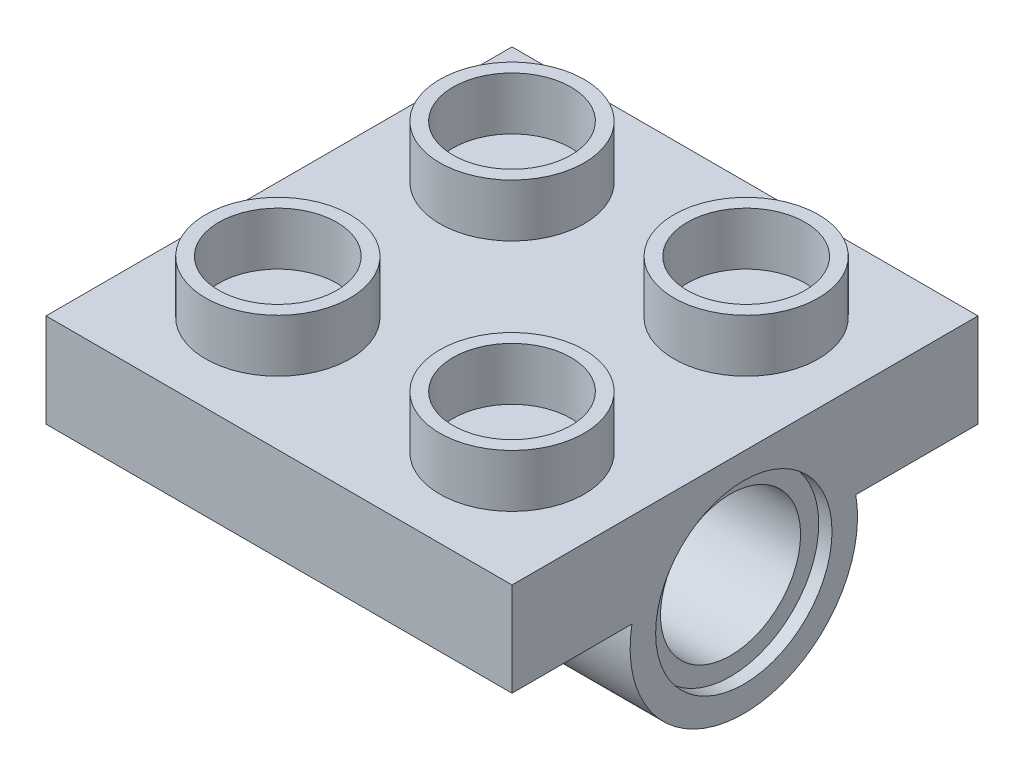
SolidWorks part; units mm, degrees
ref_plane "Front Plane" through (0, 0, 0) normal (0, 0, 1) x (1, 0, 0)
ref_plane "Top Plane" through (0, 0, 0) normal (0, 1, 0) x (1, 0, 0)
ref_plane "Right Plane" through (0, 0, 0) normal (1, 0, 0) x (0, 0, -1)
sketch "Sketch1" plane through (0, 0, 0) normal (0, 1, 0) x (1, 0, 0)
  line L1 (-7.9, 7.9) -> (7.9, 7.9)
  line L2 (-7.9, 7.9) -> (-7.9, -7.9)
  line L3 (-7.9, -7.9) -> (7.9, -7.9)
  line L4 (7.9, 7.9) -> (7.9, -7.9)
  line L5 (-7.9, 7.9) -> (7.9, -7.9) construction
  line L6 (-7.9, -7.9) -> (7.9, 7.9) construction
  point P0 (0, 0)
  dimension "D1" = 15.8
  dimension "D2" = 15.8
extrude "Boss-Extrude1" add sketch "Sketch1" against normal blind 7.71
sketch "Sketch2" plane through (7.9, 0, 0) normal (1, 0, 0) x (0, 0, -1)
  line L0 (-7.9, 0) -> (7.9, 0) construction
  line L2 (7.9, -7.71) -> (7.9, 0) construction
  circle A0 centre (-0.04, -3.855) radius 2.99
  dimension "D3" = 5.98
  dimension "D1" = 3.855
  dimension "D2" = 7.94
extrude "Cut-Extrude1" cut sketch "Sketch2" against normal blind 0.45
sketch "Sketch3" plane through (7.45, 0, 0) normal (1, 0, 0) x (0, 0, -1)
  line L0 (-7.9, 0) -> (7.9, 0) construction
  line L1 (7.9, -7.71) -> (7.9, 0) construction
  circle A0 centre (-0.04, -3.855) radius 2.375
  dimension "D2" = 7.94
  dimension "D3" = 4.75
  dimension "D1" = 3.855
extrude "Cut-Extrude2" cut sketch "Sketch3" against normal blind 6.56
sketch "Sketch4" plane through (7.9, 0, 0) normal (1, 0, 0) x (0, 0, -1)
  line L0 (-7.9, -3.18) -> (-3.8354, -3.18)
  line L1 (-7.9, -7.71) -> (-7.9, 0) construction
  line L2 (3.7554, -3.18) -> (7.9, -3.18)
  line L3 (7.9, -7.71) -> (7.9, 0) construction
  line L4 (-7.9, 0) -> (7.9, 0) construction
  arc A0 (-3.8354, -3.18) -> (3.7554, -3.18) centre (-0.04, -3.855) ccw
  dimension "D2" = 3.855
  dimension "D1" = 3.18
extrude "Cut-Extrude4" cut sketch "Sketch4" against normal through all and the other way through all flip side to cut
sketch "Sketch6" plane through (-7.9, 0, 0) normal (-1, 0, 0) x (0, 0, 1)
  line L0 (-3.7554, -3.18) -> (3.8354, -3.18)
extrude "Cut-Extrude5" cut sketch "Sketch6" against normal blind 8.87 and the other way through all flip side to cut
sketch "Sketch7" plane through (0, -3.18, 0) normal (0, -1, 0) x (1, 0, 0)
  line L2 (6.41, 6.33) -> (-0.33, 6.33)
  line L3 (-0.33, 6.33) -> (-0.33, -6.33)
  line L4 (-0.33, -6.33) -> (6.41, -6.33)
  line L19 (6.41, 6.33) -> (6.41, 4.0505)
  line L20 (6.41, 4.0505) -> (0.97, 4.0505)
  line L21 (0.97, 4.0505) -> (0.97, -4.2172)
  line L22 (0.97, -4.2172) -> (6.41, -4.2172)
  line L23 (6.41, -4.2172) -> (6.41, -6.33)
  line L24 (7.9, 3.8354) -> (7.9, 7.9) construction
  line L25 (7.9, 7.9) -> (-7.9, 7.9) construction
  line L26 (7.9, -7.9) -> (7.9, -3.7554) construction
  line L27 (-7.9, -7.9) -> (7.9, -7.9) construction
  dimension "D1" = 1.49
  dimension "D2" = 1.57
  dimension "D3" = 1.49
  dimension "D4" = 1.57
  dimension "D5" = 6.74
extrude "Cut-Extrude6" cut sketch "Sketch7" against normal blind 2.07
sketch "Sketch10" plane through (0, -3.18, 0) normal (0, -1, 0) x (1, 0, 0)
  line L0 (0.97, 3.8354) -> (0.97, 4.0505)
  line L1 (0.97, 4.0505) -> (6.41, 4.0505)
  line L2 (6.41, 4.0505) -> (6.41, 3.8354)
  line L3 (7.9, 3.8354) -> (0.97, 3.8354) construction
  line L4 (6.41, 3.8354) -> (0.97, 3.8354)
extrude "Cut-Extrude8" cut sketch "Sketch10" against normal up to surface (2.07 mm away) up to face at (3.365, -1.11, -0.0417)
sketch "Sketch11" plane through (0, -3.18, 0) normal (0, -1, 0) x (1, 0, 0)
  line L0 (6.41, -4.2172) -> (0.97, -4.2172)
  line L1 (0.97, -4.2172) -> (0.97, -3.7554)
  line L2 (0.97, -3.7554) -> (6.41, -3.7554)
  line L3 (7.9, -3.7554) -> (0.97, -3.7554) construction
  line L4 (6.41, -3.7554) -> (6.41, -4.2172)
extrude "Cut-Extrude9" cut sketch "Sketch11" against normal up to surface (2.07 mm away) up to face at (3.365, -1.11, -0.0954)
sketch "Sketch12" plane through (0, -3.18, 0) normal (0, -1, 0) x (1, 0, 0)
  line L0 (-6.41, 6.47) -> (-1.48, 6.47)
  line L1 (-1.48, 6.47) -> (-1.48, -6.47)
  line L2 (-1.48, -6.47) -> (-6.41, -6.47)
  line L3 (-6.41, -6.47) -> (-6.41, 6.47)
  line L4 (-0.33, 6.33) -> (-0.33, -6.33) construction
  line L5 (-7.9, 7.9) -> (-7.9, -7.9) construction
  line L6 (7.9, 7.9) -> (-7.9, 7.9) construction
  line L7 (-7.9, -7.9) -> (7.9, -7.9) construction
  dimension "D1" = 1.15
  dimension "D2" = 1.49
  dimension "D3" = 1.43
  dimension "D4" = 1.43
extrude "Cut-Extrude10" cut sketch "Sketch12" against normal blind 2.07
sketch "Sketch13" plane through (0, -1.11, 0) normal (0, -1, 0) x (1, 0, 0)
  line L1 (7.9, 7.9) -> (-7.9, 7.9) construction
  line L2 (-6.41, 6.47) -> (-6.41, -6.47) construction
  circle A0 centre (-3.985, -0.04) radius 1.425
  circle A1 centre (-3.985, -0.04) radius 1.1
  dimension "D1" = 7.94
  dimension "D2" = 2.85
  dimension "D3" = 2.425
  dimension "D4" = 2.2
extrude "Boss-Extrude2" add sketch "Sketch13" along normal offset from surface (1.87 mm away) 0.2 up to face at (-3.945, -3.18, 0)
sketch "Sketch14" plane through (0, 0, 0) normal (0, 1, 0) x (1, 0, 0)
  line L1 (7.9, 7.9) -> (-7.9, 7.9) construction
  line L2 (-7.9, 7.9) -> (-7.9, -7.9) construction
  circle A0 centre (-3.93, 3.93) radius 2.45
  circle A2 centre (-3.93, 3.93) radius 2
  circle A3 centre (4.01, 3.93) radius 2
  circle A4 centre (4.01, 3.93) radius 2.45
  circle A5 centre (-3.93, -4.01) radius 2
  circle A6 centre (-3.93, -4.01) radius 2.45
  circle A7 centre (4.01, -4.01) radius 2
  circle A8 centre (4.01, -4.01) radius 2.45
  dimension "D1" = 3.97
  dimension "D2" = 3.97
  dimension "D3" = 4.9
  dimension "D4" = 4
  dimension "D7" = 7.94
  dimension "D8" = 7.94
  dimension "D5" = 2
  dimension "D6" = 2
extrude "Boss-Extrude3" add sketch "Sketch14" along normal blind 1.79
